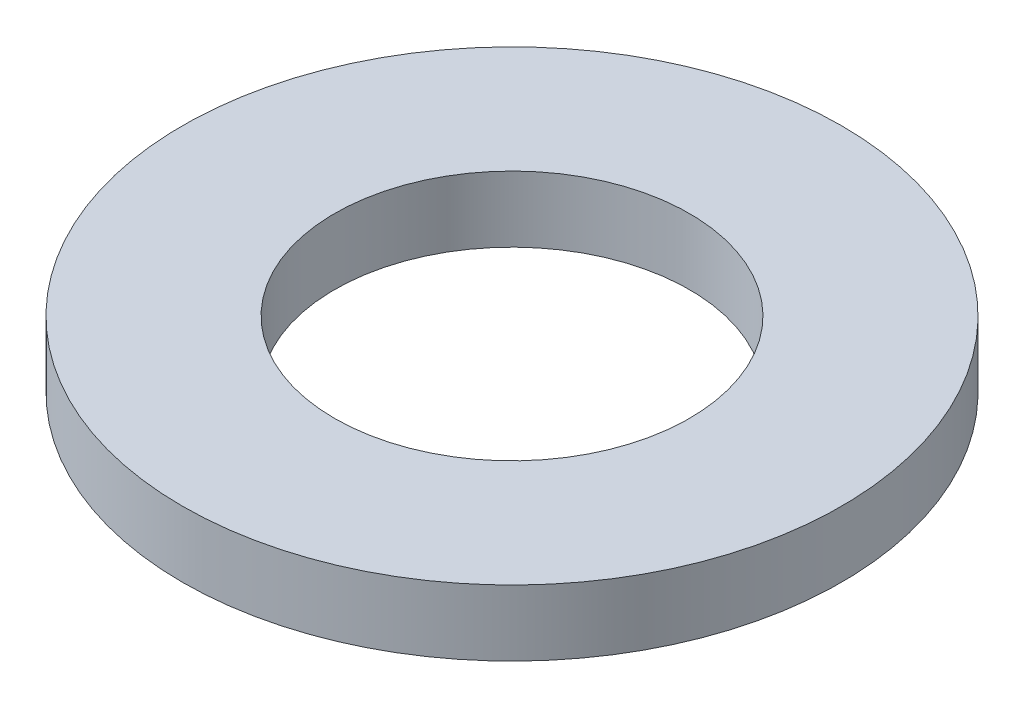
SolidWorks part; units mm, degrees
material "AISI 316 Нержавеющая сталь, лист (SS)"
ref_plane "Спереди" through (0, 0, 0) normal (0, 0, 1) x (1, 0, 0)
ref_plane "Сверху" through (0, 0, 0) normal (0, 1, 0) x (1, 0, 0)
ref_plane "Справа" through (0, 0, 0) normal (1, 0, 0) x (0, 0, -1)
sketch "Эскиз1" plane through (0, 0, 0) normal (0, 1, 0) x (1, 0, 0)
  circle A0 centre (0, 0) radius 5.385
  circle A1 centre (0, 0) radius 10
  dimension "D1" = 10.77
  dimension "D2" = 20
extrude "Бобышка-Вытянуть1" add sketch "Эскиз1" along normal blind 2
